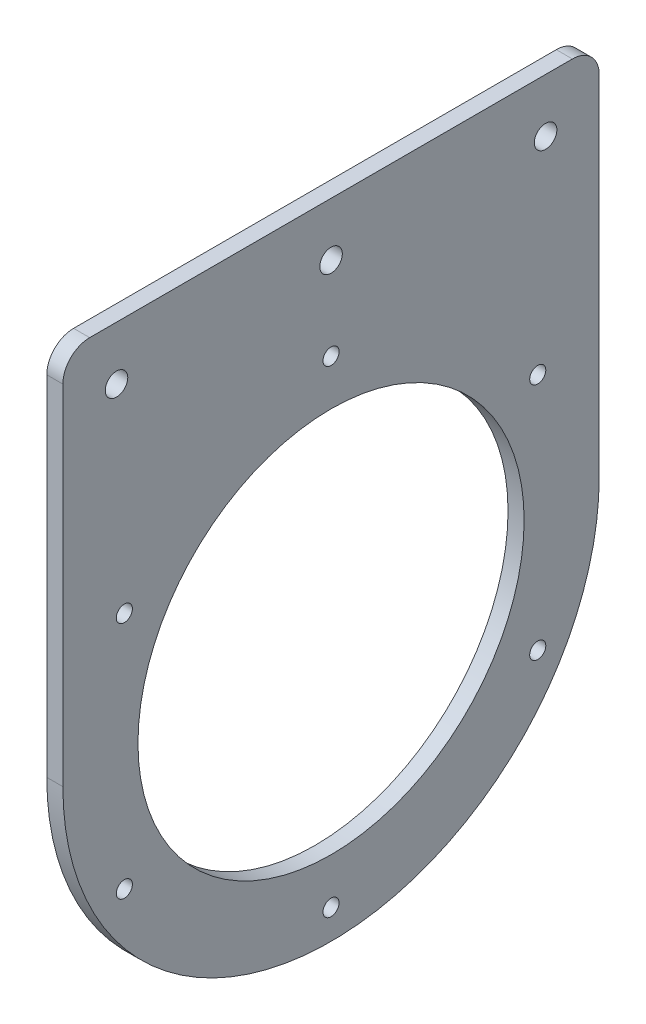
SolidWorks part; units mm, degrees
ref_plane "前视基准面" through (0, 0, 0) normal (0, 0, 1) x (1, 0, 0)
ref_plane "上视基准面" through (0, 0, 0) normal (0, 1, 0) x (1, 0, 0)
ref_plane "右视基准面" through (0, 0, 0) normal (1, 0, 0) x (0, 0, -1)
other "Configuration Table"
sketch "草图1" plane through (0, 0, 0) normal (1, 0, 0) x (0, 0, -1)
  circle A0 centre (0, 0) radius 36
  circle A1 centre (0, 0) radius 50
  dimension "D1" = 72
  dimension "D2" = 100
extrude "凸台-拉伸1" add sketch "草图1" along normal blind 3
sketch "草图2" plane through (3, 0, 0) normal (1, 0, 0) x (0, 0, -1)
  line L0 (-50, 0) -> (-50, 70)
  line L1 (-50, 70) -> (50, 70)
  line L2 (50, 70) -> (50, 0)
  circle A0 centre (0, 0) radius 50 construction
  circle A2 centre (0, 0) radius 50
  arc A3 (50, 0) -> (-50, 0) centre (0, 0) ccw
  dimension "D1" = 0
  dimension "D2" = 70
extrude "凸台-拉伸2" add sketch "草图2" against normal blind 3
sketch "草图3" plane through (3, 0, 0) normal (1, 0, 0) x (0, 0, -1)
  circle A0 centre (0, 0) radius 44.5 construction
  circle A1 centre (0, 44.5) radius 1.5
  circle A2 centre (38.5381, 22.25) radius 1.5
  circle A3 centre (38.5381, -22.25) radius 1.5
  circle A4 centre (0, -44.5) radius 1.5
  circle A5 centre (-38.5381, -22.25) radius 1.5
  circle A6 centre (-38.5381, 22.25) radius 1.5
  point P18 (0, 0)
  dimension "D1" = 89
  dimension "D2" = 3
  dimension "D3" = 6
extrude "切除-拉伸1" cut sketch "草图3" against normal blind 3
sketch "草图4" plane through (3, 0, 0) normal (1, 0, 0) x (0, 0, -1)
  line L0 (-50, 60) -> (50, 60) construction
  line L1 (-50, 70) -> (-50, 0) construction
  line L2 (50, 0) -> (50, 70) construction
  line L3 (50, 70) -> (-50, 70) construction
  circle A0 centre (-40, 60) radius 2.1
  circle A1 centre (0, 60) radius 2.1
  circle A2 centre (40, 60) radius 2.1
  dimension "D2" = 4.2
  dimension "D5" = 40
  dimension "D1" = 10
  dimension "D3" = 10
  dimension "D4" = 3
extrude "切除-拉伸2" cut sketch "草图4" against normal through all
fillet "圆角2" radius 5 2 edges at (1.5, 70, -50) (1.5, 70, 50)
